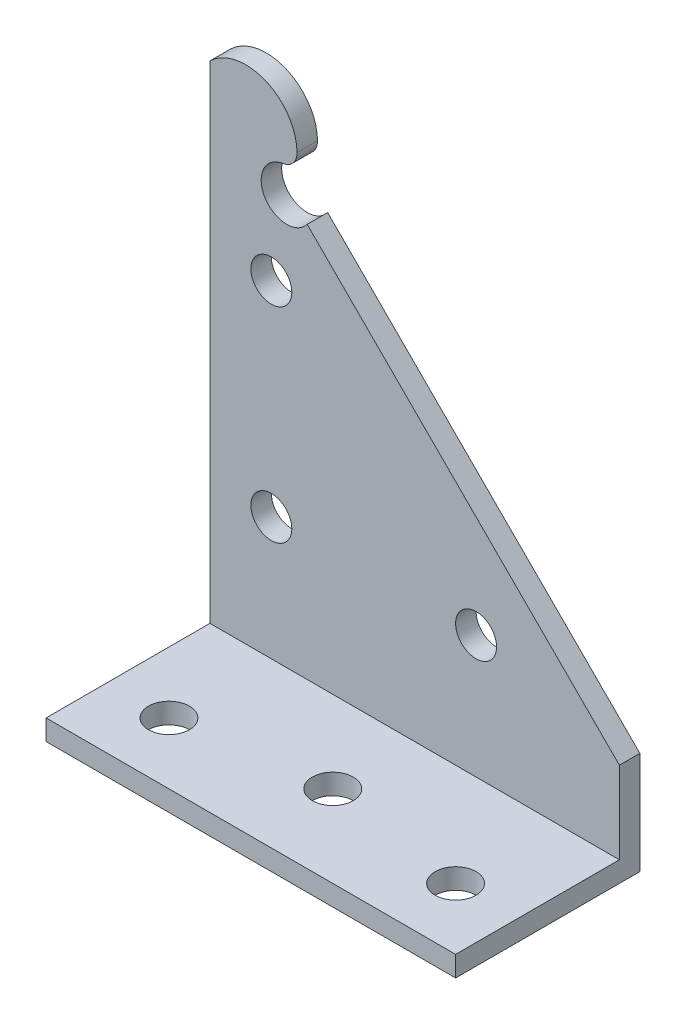
SolidWorks part; units mm, degrees
ref_plane "Front Plane" through (0, 0, 0) normal (0, 0, 1) x (1, 0, 0)
ref_plane "Top Plane" through (0, 0, 0) normal (0, 1, 0) x (1, 0, 0)
ref_plane "Right Plane" through (0, 0, 0) normal (1, 0, 0) x (0, 0, -1)
sketch "Sketch1" plane through (0, 0, 0) normal (0, 0, 1) x (1, 0, 0)
  line L0 (0, 0) -> (0, 38898.0095) construction
  line L1 (0, 0) -> (-38898.0095, 0) construction
  line L2 (0, 0) -> (0, 119.3766)
  line L3 (0, 0) -> (63.5, 0)
  line L4 (63.5, 0) -> (63.5, 15.875)
  line L6 (63.5, 15.875) -> (15.0803, 64.2947)
  circle A3 centre (9.525, 22.225) radius 3.175
  circle A4 centre (9.525, 53.975) radius 3.175
  circle A5 centre (41.275, 22.225) radius 3.175
  arc A6 (0, 78.7051) -> (13.5118, 73.1485) centre (5.5626, 73.025) cw
  arc A7 (11.3395, 70.5957) -> (15.0803, 64.2947) centre (11.9126, 66.675) ccw
  arc A8 (13.5118, 73.1485) -> (11.3395, 70.5957) centre (10.9721, 73.109) cw
  point P14 (12.964, 66.6191)
  point P15 (16.5616, 62.7971)
  point P21 (11.9126, 62.8244)
  dimension "D2" = 6.35
  dimension "D3" = 6.35
  dimension "D4" = 6.35
  dimension "D15" = 7.9502
  dimension "D16" = 19.05
  dimension "D11" = 3.9624
  dimension "D17" = 2.54
  dimension "D1" = 63.5
  dimension "D5" = 22.225
  dimension "D6" = 31.75
  dimension "D7" = 15.875
  dimension "D8" = 9.525
  dimension "D9" = 31.75
  dimension "D10" = 45
  dimension "D12" = 5.5626
  dimension "D13" = 6.35
  dimension "D14" = 6.35
extrude "Boss-Extrude1" add sketch "Sketch1" along normal blind 3.175 contours A8 A6 L2 L3 L4 L6 A7 A5 A4 A3
sketch "Sketch2" plane through (0, 0, 3.175) normal (0, 0, 1) x (1, 0, 0)
  line L0 (0, 3.175) -> (63.5, 3.175)
  line L1 (0, 0) -> (0, 78.7051) construction
  line L2 (63.5, 0) -> (63.5, 15.875) construction
  line L3 (63.5, 3.175) -> (63.5, 0)
  line L4 (63.5, 0) -> (0, 0)
  line L5 (0, 0) -> (0, 3.175)
  dimension "D1" = 3.175
extrude "Boss-Extrude2" add sketch "Sketch2" along normal blind 25.4
sketch "Sketch3" plane through (0, 3.175, 0) normal (0, 1, 0) x (1, 0, 0)
  line L0 (31.75, -28.575) -> (31.75, 49971.425) construction
  line L1 (63.5, -28.575) -> (0, -28.575) construction
  line L2 (0, -28.575) -> (0, -3.175) construction
  line L3 (63.5, -28.575) -> (63.5, -3.175) construction
  circle A0 centre (9.525, -19.05) radius 3.175
  circle A1 centre (53.975, -19.05) radius 3.175
  circle A2 centre (31.75, -15.875) radius 3.175
  point P10 (31.75, -28.575)
  dimension "D1" = 6.35
  dimension "D2" = 9.525
  dimension "D3" = 9.525
  dimension "D4" = 9.525
  dimension "D5" = 9.525
  dimension "D6" = 0
  dimension "D7" = 3.175
extrude "Cut-Extrude1" cut sketch "Sketch3" against normal through all both and the other way through all
